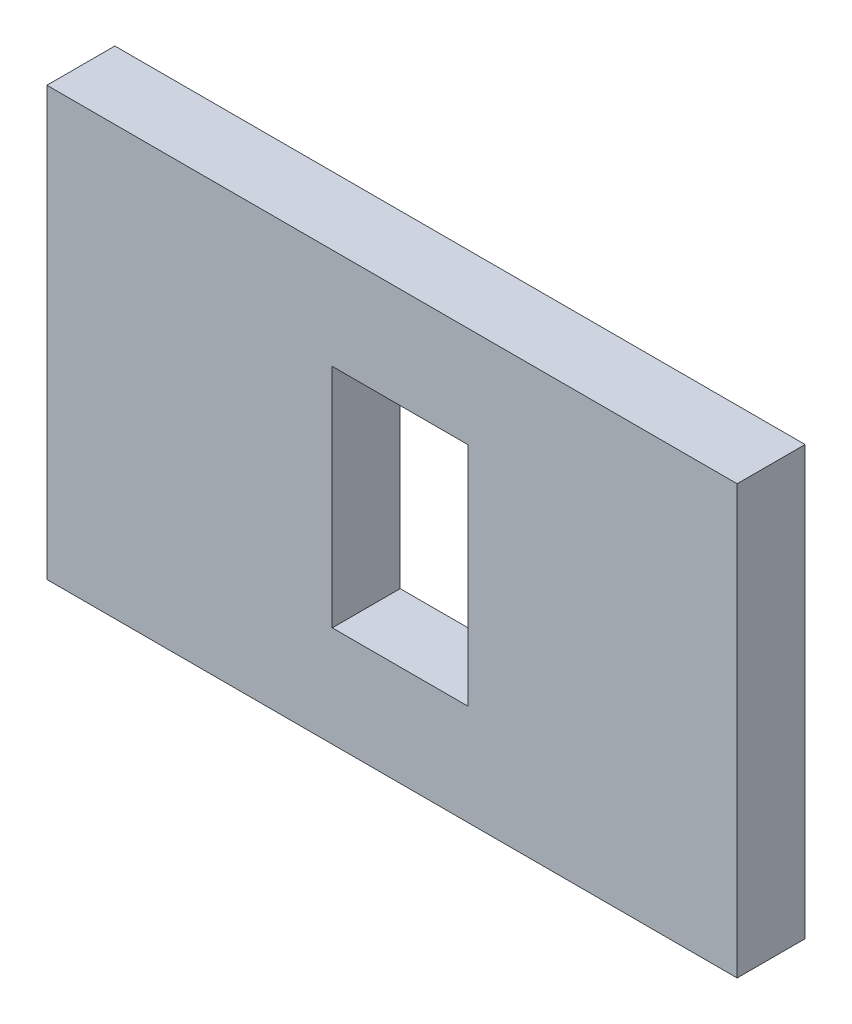
SolidWorks part; units mm, degrees
ref_plane "Front Plane" through (0, 0, 0) normal (0, 0, 1) x (1, 0, 0)
ref_plane "Top Plane" through (0, 0, 0) normal (0, 1, 0) x (1, 0, 0)
ref_plane "Right Plane" through (0, 0, 0) normal (1, 0, 0) x (0, 0, -1)
sketch "Sketch1" plane through (0, 0, 0) normal (0, 0, 1) x (1, 0, 0)
  line L5 (89, 28.9) -> (101, 28.9)
  line L6 (63.8024, 37.8) -> (124.7559, 37.8)
  line L8 (63.8024, 37.8) -> (63.8024, 0)
  line L9 (63.8024, 0) -> (124.7559, 0)
  line L72 (124.7559, 37.8) -> (124.7559, 0)
  line L78 (89, 28.9) -> (89, 8.9)
  line L79 (89, 8.9) -> (101, 8.9)
  line L80 (101, 28.9) -> (101, 8.9)
  dimension "D13" = 12
  dimension "D14" = 20
extrude "Boss-Extrude1" add sketch "Sketch1" along normal blind 6
